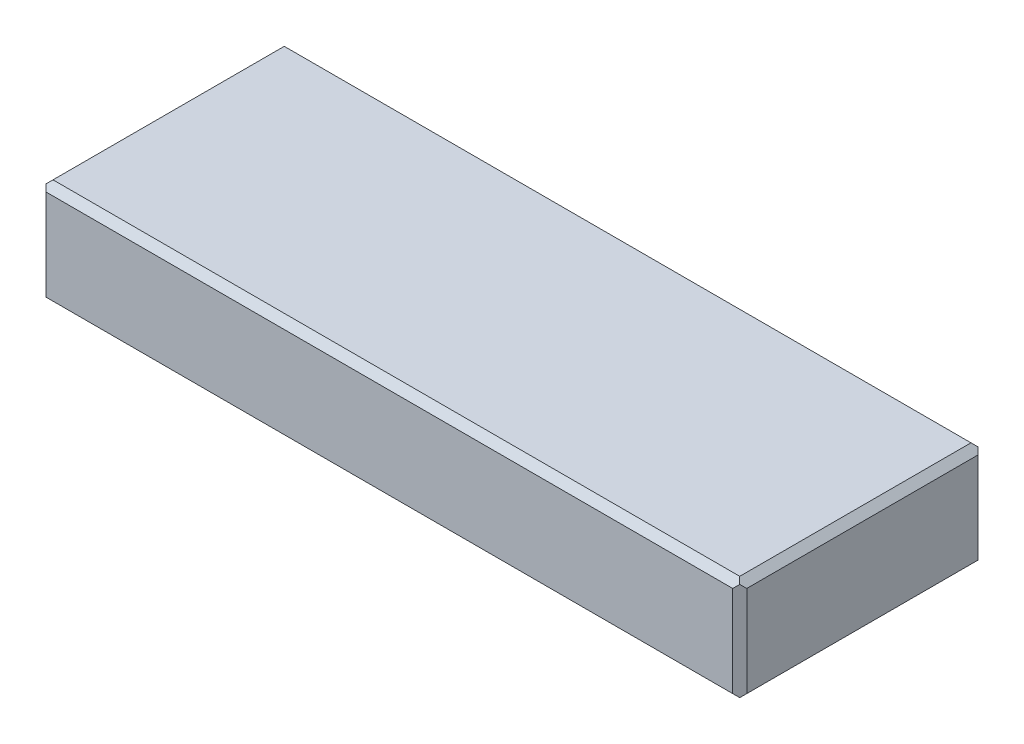
SolidWorks part; units mm, degrees
ref_plane "Plan de face" through (0, 0, 0) normal (0, 0, 1) x (1, 0, 0)
ref_plane "Plan de dessus" through (0, 0, 0) normal (0, 1, 0) x (1, 0, 0)
ref_plane "Plan de droite" through (0, 0, 0) normal (1, 0, 0) x (0, 0, -1)
sketch "Esquisse1" plane through (0, 0, 0) normal (0, 0, 1) x (1, 0, 0)
  line L1 (-49.1219, 29.1511) -> (150.8781, 29.1511)
  line L2 (-49.1219, 29.1511) -> (-49.1219, -0.8489)
  line L3 (-49.1219, -0.8489) -> (150.8781, -0.8489)
  line L4 (150.8781, 29.1511) -> (150.8781, -0.8489)
  dimension "D1" = 200
  dimension "D2" = 30
extrude "Extrusion1" add sketch "Esquisse1" along normal blind 70
chamfer "Chanfrein1" distance 2 angle 45 4 edges at (-49.1219, -0.8489, 35) (50.8781, -0.8489, 0) (50.8781, -0.8489, 70) (150.8781, -0.8489, 35)
chamfer "Chanfrein2" distance 2 angle 45 4 edges at (-49.1219, 29.1511, 35) (50.8781, 29.1511, 70) (150.8781, 29.1511, 35) (50.8781, 29.1511, 0)
chamfer "Chanfrein3" distance 2 angle 45 4 edges at (-49.1219, 14.1511, 70) (150.8781, 14.1511, 70) (150.8781, 14.1511, 0) (-49.1219, 14.1511, 0)
